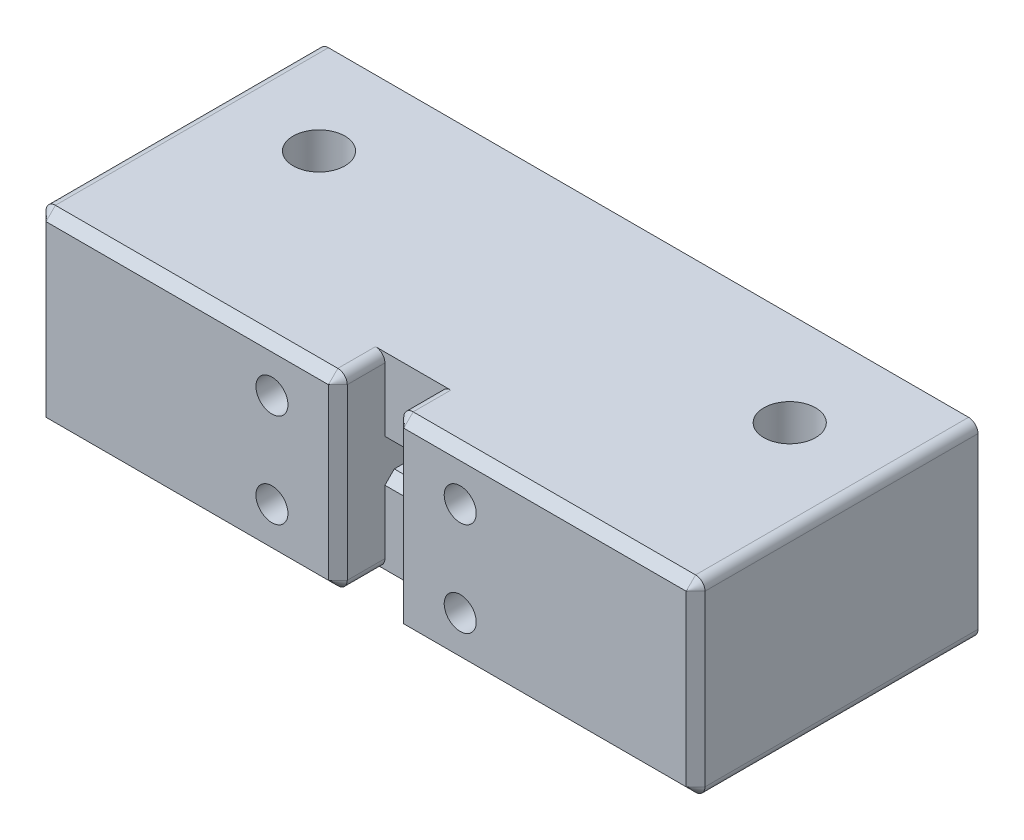
SolidWorks part; units mm, degrees
ref_plane "Front Plane" through (0, 0, 0) normal (0, 0, 1) x (1, 0, 0)
ref_plane "Top Plane" through (0, 0, 0) normal (0, 1, 0) x (1, 0, 0)
ref_plane "Right Plane" through (0, 0, 0) normal (1, 0, 0) x (0, 0, -1)
ref_plane "Front Of Part Plane" through (0, 0, 25) normal (0, 0, 1) x (1, 0, 0)
ref_plane "Thicker Section Plane" through (0, 0, 30) normal (0, 0, 1) x (1, 0, 0)
sketch "Main Block Sketch" plane through (0, 0, 0) normal (0, 0, 1) x (1, 0, 0)
  line L0 (-25, 0) -> (25, 0) construction
  line L1 (-35, -10) -> (35, -10)
  line L2 (-35, -10) -> (-35, 10)
  line L3 (-35, 10) -> (35, 10)
  line L4 (35, -10) -> (35, 10)
  line L5 (-35, -10) -> (35, 10) construction
  line L6 (-35, 10) -> (35, -10) construction
  line L7 (-10, 5) -> (10, 5) construction
  line L8 (-10, -5) -> (10, -5) construction
  point P0 (0, 0)
  point P9 (0, 0)
  point P12 (0, 0)
  dimension "D1" = 20
  dimension "D2" = 70
  dimension "D3" = 50
  dimension "D4" = 20
  dimension "D5" = 5
extrude "Main Block" add sketch "Main Block Sketch" along normal up to surface (25 mm away) up to plane "Front Of Part Plane"
sketch "Thicker Section Sketch" plane through (0, 0, 25) normal (0, 0, 1) x (1, 0, 0)
  line L0 (0, 10) -> (0, -10) construction
  line L1 (-35, 10) -> (35, 10) construction
  line L2 (-35, -10) -> (35, -10) construction
  line L3 (3, 10) -> (3, -10)
  line L4 (-35, 10) -> (-3, 10)
  line L5 (-35, 10) -> (-35, -10)
  line L6 (-35, -10) -> (-3, -10)
  line L7 (-3, 10) -> (-3, -10)
  line L8 (35, -10) -> (3, -10)
  line L9 (35, 10) -> (35, -10)
  line L10 (35, 10) -> (3, 10)
  dimension "D1" = 3
extrude "Thicker Section" add sketch "Thicker Section Sketch" along normal up to surface (5 mm away) up to plane "Thicker Section Plane"
sketch "Mounting Holes Sketch" plane through (0, 0, 0) normal (0, 1, 0) x (1, 0, 0)
  line L0 (-25, -10) -> (25, -10)
  point P3 (0, -10)
  dimension "D1" = 50
  dimension "D2" = 10
sketch "Belt Trap Cut Sketch" plane through (0, 0, 25) normal (0, 0, 1) x (1, 0, 0)
  line L1 (-3, -1.25) -> (3, -1.25)
  line L2 (-3, -1.25) -> (-3, 1.25)
  line L3 (-3, 1.25) -> (3, 1.25)
  line L4 (3, -1.25) -> (3, 1.25)
  line L5 (-3, -1.25) -> (3, 1.25) construction
  line L6 (-3, 1.25) -> (3, -1.25) construction
  line L7 (3, 10) -> (3, -10) construction
  dimension "D1" = 2.5
  dimension "D2" = 6
extrude "Belt Trap Cut" cut sketch "Belt Trap Cut Sketch" against normal through all
hole_wizard "Belt Holder Mounting Holes" positions "Sketch6" profile "Sketch7" hole size "M3" standard "ISO" end condition through all
sketch "Sketch6" plane through (0, 0, 30) normal (0, 0, 1) x (1, 0, 0)
  point P2 (-10, 5)
  point P5 (10, 5)
  point P10 (-10, -5)
  point P13 (10, -5)
sketch "Sketch7" plane through (-10, 5, 30) normal (1, 0, 0) x (0, -1, 0)
  line L0 (0, 0) -> (0, 30)
  line L1 (0, 30) -> (1.7, 30)
  line L2 (1.7, 30) -> (1.7, 0)
  line L5 (1.7, 0) -> (0, 0)
  line L11 (0, -6.35) -> (0, 107.95) construction
  dimension "Thru Hole Dia." = 3.4
  dimension "Thru Hole Depth" = 30
sketch "Nut Trap Sketch" plane through (0, 0, 0) normal (0, 0, 1) x (1, 0, 0)
  line L0 (-25, 0) -> (25, 0) construction
  line L1 (11.5588, 7.7) -> (8.4412, 7.7)
  line L2 (8.4412, 7.7) -> (6.8823, 5)
  line L3 (6.8823, 5) -> (8.4412, 2.3)
  line L4 (8.4412, 2.3) -> (11.5588, 2.3)
  line L5 (11.5588, 2.3) -> (13.1177, 5)
  line L6 (13.1177, 5) -> (11.5588, 7.7)
  line L7 (-11.5588, 7.7) -> (-13.1177, 5)
  line L8 (-13.1177, 5) -> (-11.5588, 2.3)
  line L9 (-11.5588, 2.3) -> (-8.4412, 2.3)
  line L10 (-8.4412, 2.3) -> (-6.8823, 5)
  line L11 (-6.8823, 5) -> (-8.4412, 7.7)
  line L12 (-8.4412, 7.7) -> (-11.5588, 7.7)
  line L13 (-25, 0) -> (25, 0) construction
  line L14 (-8.4412, -7.7) -> (-11.5588, -7.7)
  line L15 (-6.8823, -5) -> (-8.4412, -7.7)
  line L16 (-8.4412, -2.3) -> (-6.8823, -5)
  line L17 (-11.5588, -2.3) -> (-8.4412, -2.3)
  line L18 (-13.1177, -5) -> (-11.5588, -2.3)
  line L19 (-11.5588, -7.7) -> (-13.1177, -5)
  line L20 (13.1177, -5) -> (11.5588, -7.7)
  line L21 (11.5588, -2.3) -> (13.1177, -5)
  line L22 (8.4412, -2.3) -> (11.5588, -2.3)
  line L23 (6.8823, -5) -> (8.4412, -2.3)
  line L24 (8.4412, -7.7) -> (6.8823, -5)
  line L25 (11.5588, -7.7) -> (8.4412, -7.7)
  circle A0 centre (10, 5) radius 2.7 construction
  circle A1 centre (-10, 5) radius 2.7 construction
  circle A2 centre (-10, -5) radius 2.7 construction
  circle A3 centre (10, -5) radius 2.7 construction
  dimension "D1" = 5.4
extrude "Nut Traps" cut sketch "Nut Trap Sketch" along normal blind 2.3
hole_wizard "Mounting Holes" positions "Sketch9" profile "Sketch10" counterbore size "M5" standard "ISO" end condition through all
sketch "Sketch9" plane through (0, -10, 0) normal (0, -1, 0) x (-1, 0, 0)
  point P0 (-25, -10)
  point P3 (25, -10)
sketch "Sketch10" plane through (25, -10, 10) normal (1, 0, 0) x (0, 0, -1)
  line L0 (0, 0) -> (0, 20)
  line L1 (0, 20) -> (2.75, 20)
  line L3 (2.75, 20) -> (2.75, 5.4)
  line L4 (2.75, 5.4) -> (5, 5.4)
  line L5 (5, 5.4) -> (5, 0)
  line L7 (5, 0) -> (0, 0)
  line L11 (0, -6.35) -> (0, 107.95) construction
  dimension "Thru Hole Dia." = 5.5
  dimension "Thru Hole Depth" = 20
  dimension "C'Bore Dia." = 10
  dimension "C'Bore Depth" = 5.4
fillet "Print Helper Fillets" radius 1 8 edges at (-35, -10, 15) (-35, 10, 15) (35, -10, 15) (35, 10, 15) (-3, -10, 27.5) (3, -10, 27.5) (3, 10, 27.5) (-3, 10, 27.5)
chamfer "Belt Guide Chamfers" distance 1 angle 45 2 edges at (0, 1.25, 25) (0, -1.25, 25)
chamfer "Cosmetic Chamfers" distance 1 angle 45 16 edges at (-19, -10, 30) (-3.2929, -9.7071, 30) (-34.7071, -9.7071, 30) (-3, 0, 30) (-35, 0, 30) (-3.2929, 9.7071, 30) (-34.7071, 9.7071, 30) (-19, 10, 30) (19, -10, 30) (34.7071, -9.7071, 30) (3.2929, -9.7071, 30) (35, 0, 30) (3, 0, 30) (34.7071, 9.7071, 30) (3.2929, 9.7071, 30) (19, 10, 30)
